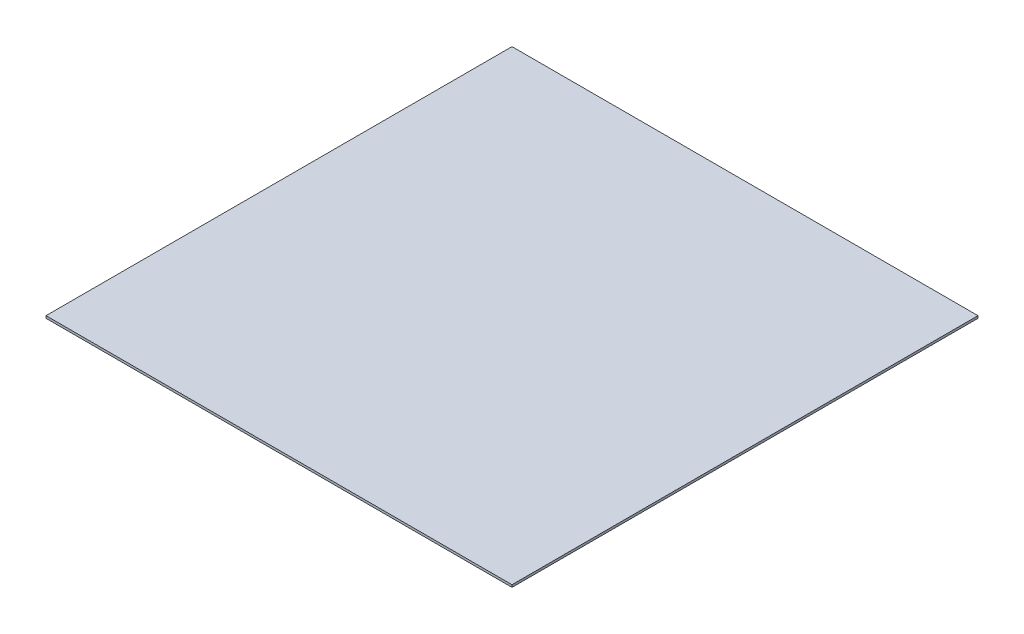
SolidWorks part; units mm, degrees
ref_plane "Front Plane" through (0, 0, 0) normal (0, 0, 1) x (1, 0, 0)
ref_plane "Top Plane" through (0, 0, 0) normal (0, 1, 0) x (1, 0, 0)
ref_plane "Right Plane" through (0, 0, 0) normal (1, 0, 0) x (0, 0, -1)
sketch "Sketch1" plane through (0, 0, 0) normal (0, 1, 0) x (1, 0, 0)
  line L1 (-100, 95.4111) -> (0, 95.4111)
  line L2 (-100, 95.4111) -> (-100, -4.5889)
  line L3 (-100, -4.5889) -> (0, -4.5889)
  line L4 (0, 95.4111) -> (0, -4.5889)
  dimension "D1" = 100
  dimension "D2" = 100
extrude "Boss-Extrude1" add sketch "Sketch1" along normal blind 0.5
